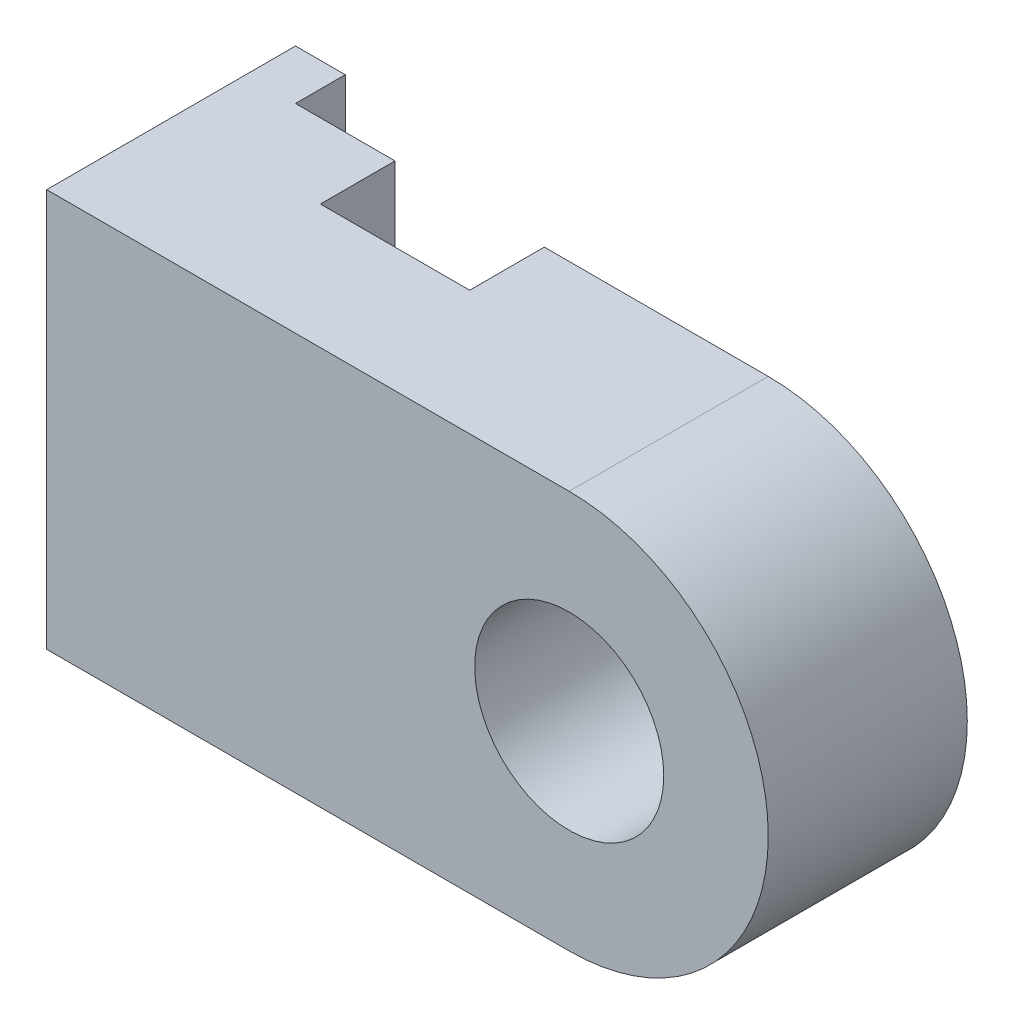
SolidWorks part; units mm, degrees
ref_plane "前视基准面" through (0, 0, 0) normal (0, 0, 1) x (1, 0, 0)
ref_plane "上视基准面" through (0, 0, 0) normal (0, 1, 0) x (1, 0, 0)
ref_plane "右视基准面" through (0, 0, 0) normal (1, 0, 0) x (0, 0, -1)
sketch "草图1" plane through (0, 0, 0) normal (0, 0, 1) x (1, 0, 0)
  line L0 (0, 4) -> (-10.5, 4)
  line L1 (-10.5, 4) -> (-10.5, -4)
  line L2 (-10.5, -4) -> (0, -4)
  circle A0 centre (0, 0) radius 1.9
  arc A1 (0, -4) -> (0, 4) centre (0, 0) ccw
  dimension "D1" = 3.8
  dimension "D2" = 8
  dimension "D3" = 10.5
extrude "凸台-拉伸1" add sketch "草图1" along normal blind 4
sketch "草图2" plane through (0, 4, 0) normal (0, 1, 0) x (1, 0, 0)
  line L0 (0, 0) -> (-10.5, 0) construction
  line L1 (-7.5, 0) -> (-4.5, 0)
  line L2 (-7.5, 0) -> (-7.5, -1.5)
  line L3 (-7.5, -1.5) -> (-4.5, -1.5)
  line L4 (-4.5, 0) -> (-4.5, -1.5)
  line L5 (-10.5, -4) -> (-10.5, 0) construction
  dimension "D1" = 3
  dimension "D2" = 3
  dimension "D3" = 1.5
extrude "切除-拉伸1" cut sketch "草图2" against normal through all
sketch "草图3" plane through (0, 0, 0) normal (0, 0, -1) x (-1, 0, 0)
  line L0 (10.5, -4) -> (7.5, -4) construction
  line L1 (10.5, 4) -> (9.5, 4)
  line L2 (10.5, 4) -> (10.5, -4)
  line L3 (10.5, -4) -> (9.5, -4)
  line L4 (9.5, 4) -> (9.5, -4)
  dimension "D1" = 1
extrude "凸台-拉伸2" add sketch "草图3" along normal blind 1
